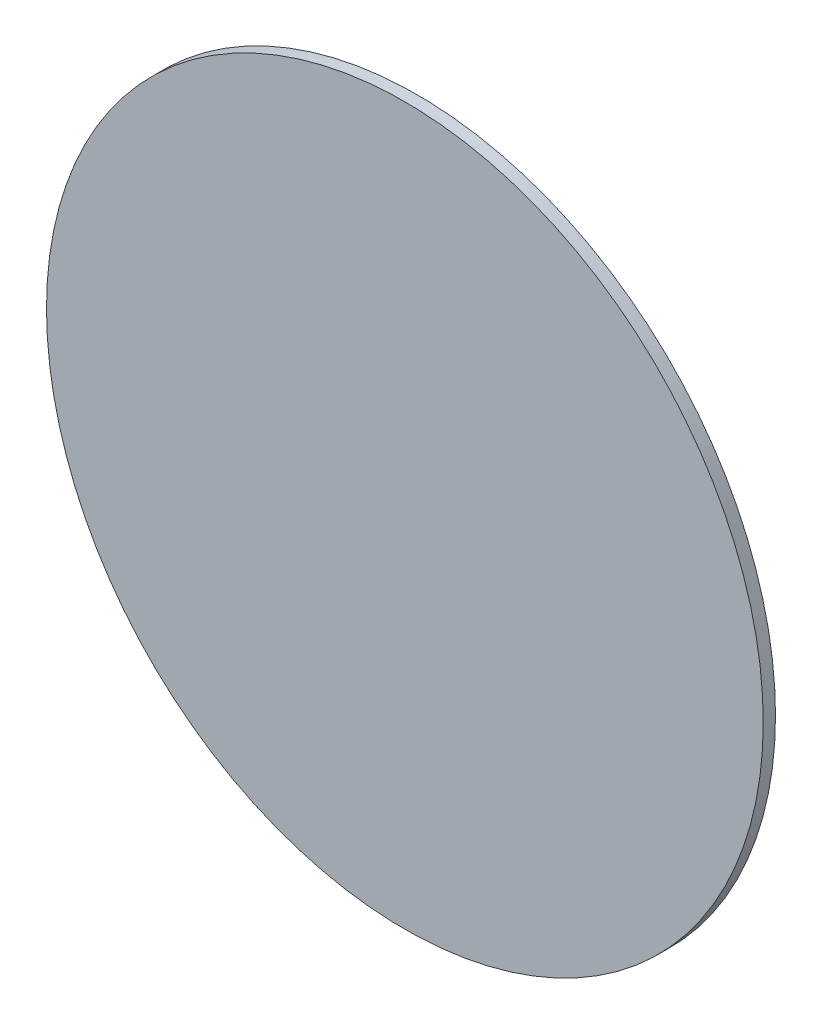
SolidWorks part; units mm, degrees
ref_plane "Front Plane" through (0, 0, 0) normal (0, 0, 1) x (1, 0, 0)
ref_plane "Top Plane" through (0, 0, 0) normal (0, 1, 0) x (1, 0, 0)
ref_plane "Right Plane" through (0, 0, 0) normal (1, 0, 0) x (0, 0, -1)
sketch "Sketch1" plane through (0, 0, 0) normal (0, 0, 1) x (1, 0, 0)
  circle A0 centre (0, 0) radius 146.4
  dimension "D1" = 292.8
extrude "Boss-Extrude1" add sketch "Sketch1" along normal blind 5
